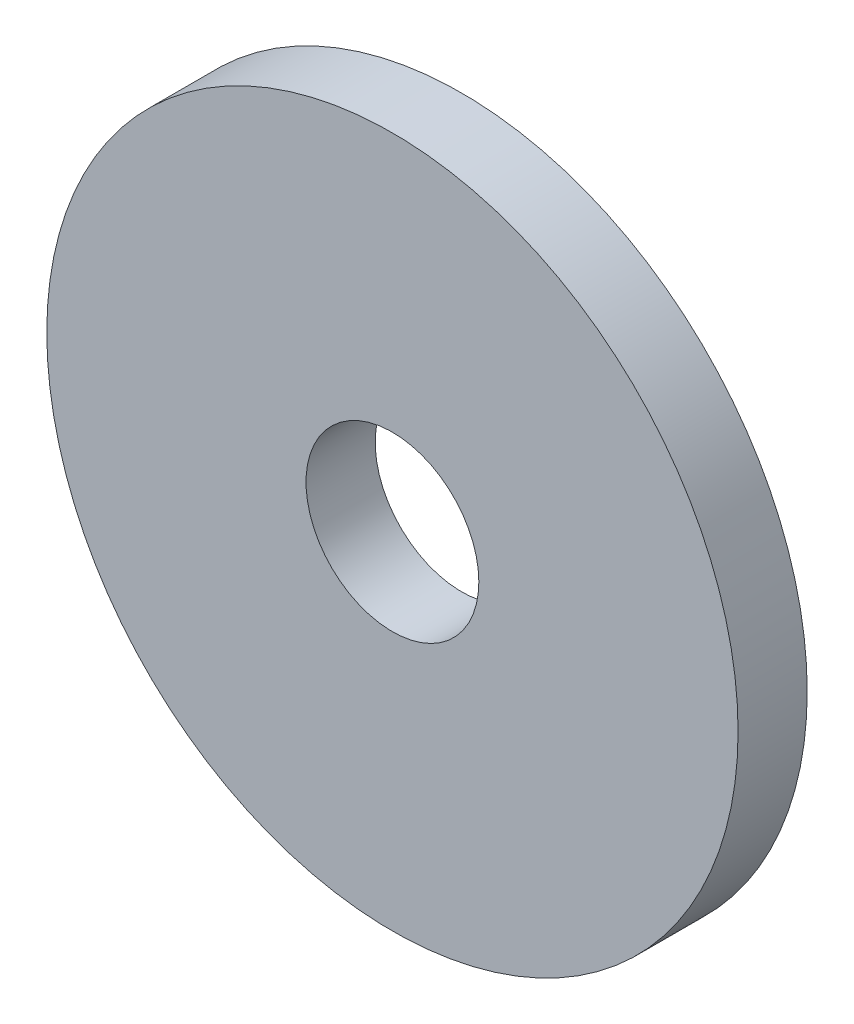
SolidWorks part; units mm, degrees
ref_plane "前视基准面" through (0, 0, 0) normal (0, 0, 1) x (1, 0, 0)
ref_plane "上视基准面" through (0, 0, 0) normal (0, 1, 0) x (1, 0, 0)
ref_plane "右视基准面" through (0, 0, 0) normal (1, 0, 0) x (0, 0, -1)
sketch "草图1" plane through (0, 0, 0) normal (0, 0, 1) x (1, 0, 0)
  circle A0 centre (0, 0) radius 10
extrude "凸台-拉伸1" add sketch "草图1" along normal blind 2
sketch "草图2" plane through (0, 0, 2) normal (0, 0, 1) x (1, 0, 0)
  circle A0 centre (0, 0) radius 2.5
  dimension "D1" = 5
extrude "切除-拉伸1" cut sketch "草图2" against normal blind 4
